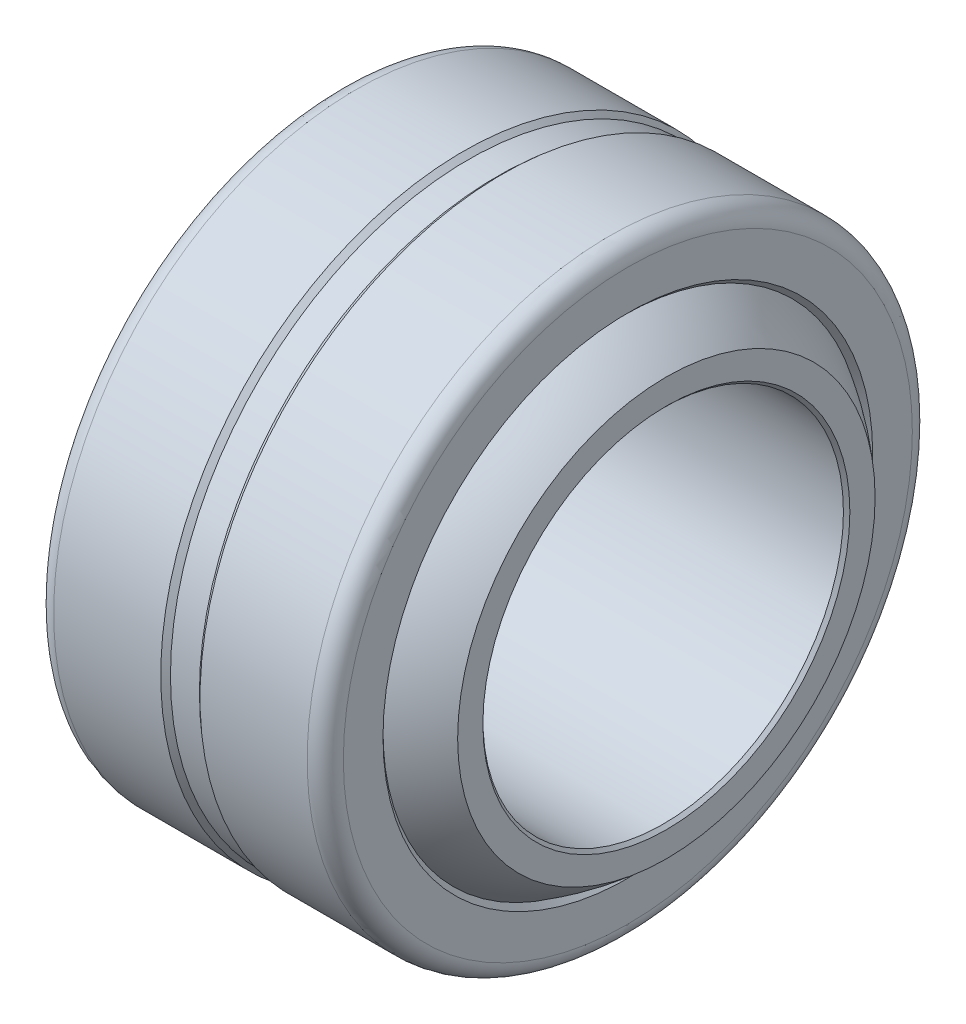
SolidWorks part; units mm, degrees
ref_plane "Front Plane" through (0, 0, 0) normal (0, 0, 1) x (1, 0, 0)
ref_plane "Top Plane" through (0, 0, 0) normal (0, 1, 0) x (1, 0, 0)
ref_plane "Right Plane" through (0, 0, 0) normal (1, 0, 0) x (0, 0, -1)
sketch "Sketch1" plane through (0, 0, 0) normal (0, 0, 1) x (1, 0, 0)
  line L0 (-45.212, 51.465) -> (-45.212, 45.2414)
  line L1 (-45.212, 45.2414) -> (-44.4206, 44.45)
  line L2 (-44.4206, 44.45) -> (44.4206, 44.45)
  line L3 (44.4206, 44.45) -> (45.212, 45.2414)
  line L4 (45.212, 45.2414) -> (45.212, 51.465)
  line L5 (34.514, 59.1739) -> (35.7124, 60.3724)
  line L6 (35.7124, 60.3724) -> (35.7124, 70.1484)
  line L7 (31.2484, 74.6125) -> (4.844, 74.6125)
  line L8 (4.844, 74.6125) -> (3.5712, 73.4933)
  line L9 (3.5712, 73.4933) -> (-3.5712, 73.4933)
  line L10 (-3.5712, 73.4933) -> (-4.844, 74.6125)
  line L11 (-4.844, 74.6125) -> (-31.2484, 74.6125)
  line L12 (-35.7124, 70.1484) -> (-35.7124, 60.3724)
  line L13 (-35.7124, 60.3724) -> (-34.514, 59.1739)
  line L14 (-45.212, 0) -> (45.212, 0) construction
  arc A0 (-34.514, 59.1739) -> (-45.212, 51.465) centre (0, 0) ccw
  arc A1 (45.212, 51.465) -> (34.514, 59.1739) centre (0, 0) ccw
  arc A2 (35.7124, 70.1484) -> (31.2484, 74.6125) centre (31.2484, 70.1484) ccw
  arc A3 (-31.2484, 74.6125) -> (-35.7124, 70.1484) centre (-31.2484, 70.1484) ccw
revolve "Revolve1" add sketch "Sketch1" angle 360 about L14
